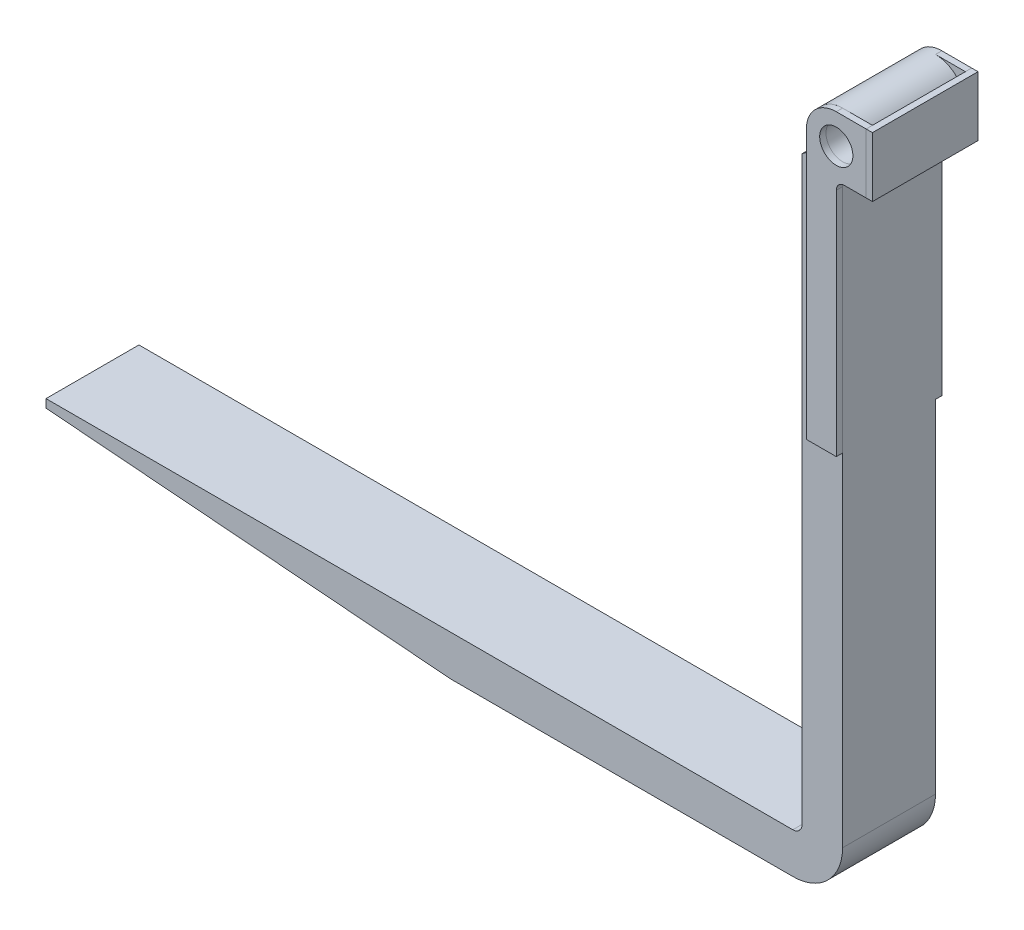
SolidWorks part; units mm, degrees
ref_plane "Front Plane" through (0, 0, 0) normal (0, 0, 1) x (1, 0, 0)
ref_plane "Top Plane" through (0, 0, 0) normal (0, 1, 0) x (1, 0, 0)
ref_plane "Right Plane" through (0, 0, 0) normal (1, 0, 0) x (0, 0, -1)
sketch "Sketch1" plane through (0, 0, 0) normal (0, 0, 1) x (1, 0, 0)
  line L0 (0, 75) -> (0, 950)
  line L1 (-75, 0) -> (-1200, 0)
  arc A0 (0, 75) -> (-75, 0) centre (-75, 75) cw
  point P6 (0, 0)
  dimension "D3" = 75
  dimension "D1" = 950
  dimension "D2" = 1200
extrude "Extrude-Thin1" add sketch "Sketch1" along normal mid plane 140 thin thin type one direction wall 61
sketch "Sketch2" plane through (0, 0, 70) normal (0, 0, 1) x (1, 0, 0)
  line L0 (-1200, 48.5) -> (-590, 0)
  line L1 (-1200, 0) -> (-1200, 61) construction
  line L2 (-75, 0) -> (-1200, 0) construction
  line L3 (-75, 61) -> (-1200, 61) construction
  dimension "D1" = 12.5
  dimension "D2" = 610
extrude "Cut-Extrude1" cut sketch "Sketch2" against normal through all and the other way through all flip side to cut
sketch "Sketch3" plane through (0, 0, 0) normal (0, 0, 1) x (1, 0, 0)
  line L0 (0, 913.8393) -> (0, 995) construction
  line L1 (0, 950) -> (0, 75) construction
  circle A0 centre (0, 995) radius 45
  circle A1 centre (0, 995) radius 25
  dimension "D1" = 90
  dimension "D2" = 50
extrude "Boss-Extrude1" add sketch "Sketch3" along normal mid plane 140 separate body
sketch "Sketch4" plane through (0, 0, 0) normal (0, 0, 1) x (1, 0, 0)
  line L0 (-61, 950) -> (0, 950) construction
  line L1 (-61, 950) -> (0, 950)
  line L2 (-61, 950) -> (-36.2126, 968.2858)
  circle A0 centre (0, 995) radius 45 construction
  circle A1 centre (0, 995) radius 45
extrude "Boss-Extrude2" add sketch "Sketch4" along normal mid plane 140 separate body contours A1 L2 L1
sketch "Sketch5" plane through (0, 0, 70) normal (0, 0, 1) x (1, 0, 0)
  line L0 (-45, 995) -> (-45, 590)
  line L1 (0, 1040) -> (45, 1040)
  line L2 (45, 1040) -> (45, 950)
  line L3 (45, 950) -> (12.5, 950)
  line L4 (0, 937.5) -> (0, 590)
  line L5 (0, 950) -> (0, 75) construction
  line L6 (0, 590) -> (-45, 590)
  circle A0 centre (0, 995) radius 45 construction
  arc A1 (-45, 995) -> (0, 1040) centre (0, 995) cw
  arc A2 (12.5, 950) -> (0, 937.5) centre (12.5, 937.5) ccw
  point P15 (0, 950)
  circle M9 centre (0, 995) radius 45
  circle M10 centre (0, 995) radius 25
  dimension "D1" = 12.5
  dimension "D2" = 45
  dimension "D3" = 450
extrude "Boss-Extrude3" add sketch "Sketch5" along normal blind 9.5 separate body contours M9 M10 | L2 L1 M9 | A2 L3 L2 L0 L6 L4 M9
mirror "Mirror1" about plane through (0, 0, 0) normal (0, 0, 1) of "Boss-Extrude3"
sketch "Sketch7" plane through (45, 0, 0) normal (1, 0, 0) x (0, 0, -1)
  line L1 (-79.5, 1040) -> (79.5, 1040)
  line L2 (-79.5, 1040) -> (-79.5, 950)
  line L3 (-79.5, 950) -> (79.5, 950)
  line L4 (79.5, 1040) -> (79.5, 950)
extrude "Boss-Extrude5" add sketch "Sketch7" along normal blind 9.5 separate body
